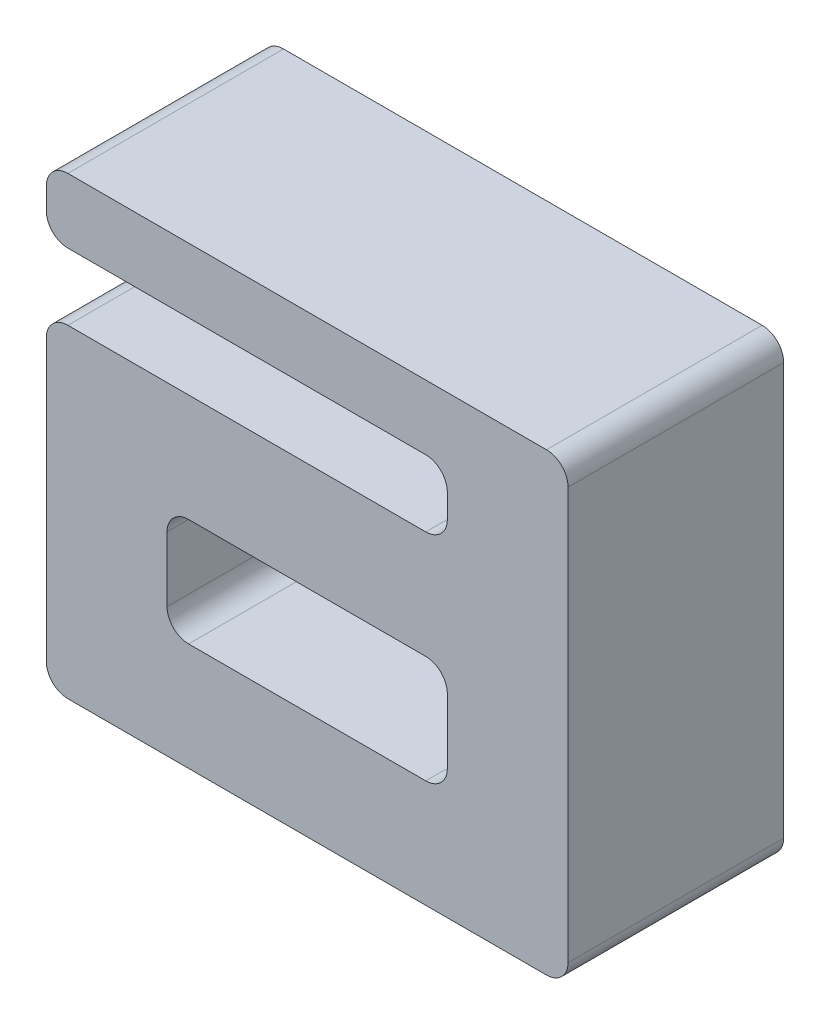
SolidWorks part; units mm, degrees
ref_plane "Front Plane" through (0, 0, 0) normal (0, 0, 1) x (1, 0, 0)
ref_plane "Top Plane" through (0, 0, 0) normal (0, 1, 0) x (1, 0, 0)
ref_plane "Right Plane" through (0, 0, 0) normal (1, 0, 0) x (0, 0, -1)
sketch "Sketch1" plane through (0, 0, 0) normal (0, 0, 1) x (1, 0, 0)
  line L0 (-3.25, 0) -> (3.25, 0) construction
  line L1 (-3.25, -1.25) -> (3.25, -1.25)
  line L2 (-3.25, -1.25) -> (-3.25, 1.25)
  line L3 (-3.25, 1.25) -> (3.25, 1.25)
  line L4 (3.25, -1.25) -> (3.25, 1.25)
  line L5 (-6.05, -3.75) -> (6.05, -3.75)
  line L6 (-6.05, -3.75) -> (-6.05, 3.75)
  line L7 (-6.05, 6.8) -> (6.05, 6.8)
  line L8 (6.05, -3.75) -> (6.05, 6.8)
  line L9 (-6.05, 5.3) -> (3.25, 5.3)
  line L11 (-6.05, 3.75) -> (3.25, 3.75)
  line L12 (3.25, 5.3) -> (3.25, 3.75)
  line L13 (0, 1.25) -> (0, -1.25) construction
  line L14 (-6.05, 5.3) -> (-6.05, 6.8)
  point P16 (0, 0)
  point P18 (-7.5664, 3.3635)
  point P19 (-7.4301, 2.051)
  dimension "D1" = 6.5
  dimension "D2" = 1.5
  dimension "D3" = 2.5
  dimension "D4" = 2.5
  dimension "D5" = 2.5
  dimension "D6" = 1.55
  dimension "D7" = 12.1
extrude "Boss-Extrude1" add sketch "Sketch1" along normal blind 5
fillet "Fillet1" radius 0.5 12 edges at (-6.05, -3.75, 2.5) (6.05, -3.75, 2.5) (6.05, 6.8, 2.5) (-6.05, 6.8, 2.5) (-6.05, 3.75, 2.5) (-6.05, 5.3, 2.5) (3.25, 3.75, 2.5) (3.25, 5.3, 2.5) (3.25, 1.25, 2.5) (3.25, -1.25, 2.5) (-3.25, -1.25, 2.5) (-3.25, 1.25, 2.5)
